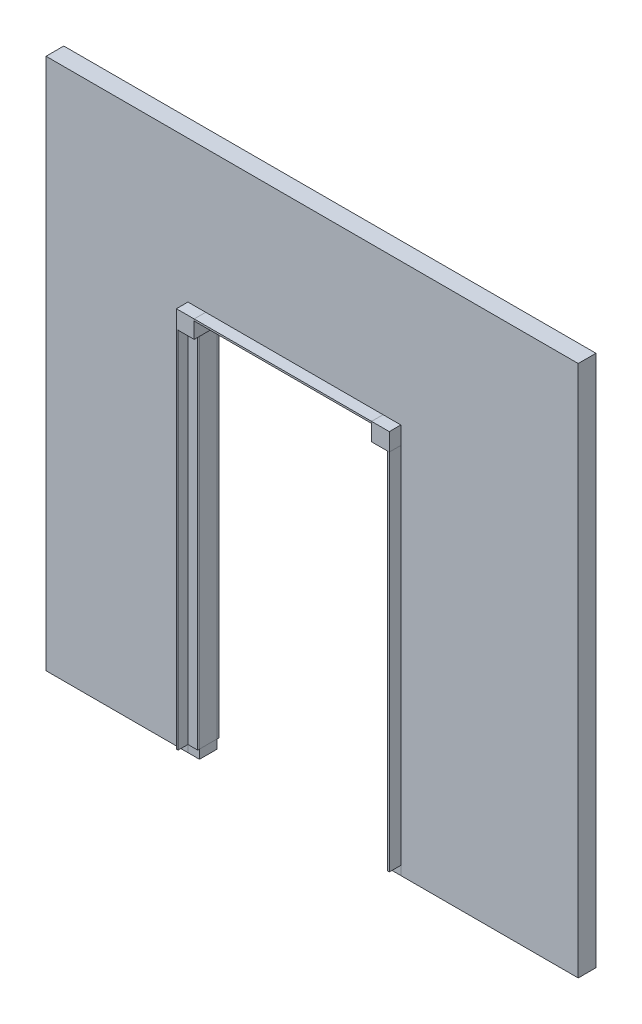
SolidWorks part; units mm, degrees
ref_plane "Front Plane" through (0, 0, 0) normal (0, 0, 1) x (1, 0, 0)
ref_plane "Top Plane" through (0, 0, 0) normal (0, 1, 0) x (1, 0, 0)
ref_plane "Right Plane" through (0, 0, 0) normal (1, 0, 0) x (0, 0, -1)
sketch "Sketch1" plane through (0, 0, 0) normal (0, 0, 1) x (1, 0, 0)
  line L1 (0, 0) -> (-3000, 0)
  line L2 (0, 0) -> (0, 3000)
  line L3 (0, 3000) -> (-3000, 3000)
  line L4 (-3000, 0) -> (-3000, 3000)
  line L5 (-2200, 2200) -> (-1000, 2200)
  line L6 (-2200, 2200) -> (-2200, 1300)
  line L7 (-2200, 1300) -> (-1000, 1300)
  line L8 (-1000, 2200) -> (-1000, 1300)
  dimension "D1" = 3000
  dimension "D2" = 3000
  dimension "D3" = 1300
  dimension "D4" = 1000
  dimension "D5" = 900
  dimension "D6" = 1200
extrude "Boss-Extrude1" add sketch "Sketch1" along normal blind 100
ref_plane "Plane4" through (0, 1750, 0) normal (0, -1, 0) x (-1, 0, 0)
ref_plane "Plane2" [suppressed] through (0, 0, 200) normal (0, 0, 1) x (1, 0, 0)
ref_plane "Plane1" through (-1600, 0, 0) normal (1, 0, 0) x (0, 0, -1)
ref_plane "Plane3" through (0, 2100, 0) normal (0, -1, 0) x (-1, 0, 0)
sketch "Sketch19" plane through (0, 0, 100) normal (0, 0, 1) x (1, 0, 0)
  line L14 (-2200, 2200) -> (-2100, 2200)
  line L15 (-2200, 2200) -> (-2200, 2100)
  line L16 (-2200, 2100) -> (-2100, 2100)
  line L17 (-2100, 2200) -> (-2100, 2100)
  line L18 (-1100, 2200) -> (-1100, 2100)
  line L19 (-1000, 2100) -> (-1100, 2100)
  line L20 (-1000, 2200) -> (-1000, 2100)
  line L21 (-1000, 2200) -> (-1100, 2200)
extrude "Boss-Extrude19" add sketch "Sketch19" along normal blind 65 and the other way blind 165 separate body
sketch "Sketch21" plane through (-2100, 0, 0) normal (1, 0, 0) x (0, 0, -1)
  line L17 (0, 2200) -> (0, 1300) construction
  line L18 (0, 2200) -> (0, 1300) construction
  line L20 (-165, 2200) -> (-100, 2200)
  line L21 (-100, 2200) -> (-100, 2135)
  line L22 (-100, 2135) -> (-110, 2135)
  line L23 (-110, 2135) -> (-110, 2190)
  line L24 (-110, 2190) -> (-165, 2190)
  line L25 (-165, 2190) -> (-165, 2200)
  line L26 (65, 2190) -> (65, 2200)
  line L27 (10, 2190) -> (65, 2190)
  line L28 (10, 2135) -> (10, 2190)
  line L29 (0, 2135) -> (10, 2135)
  line L30 (65, 2200) -> (0, 2200)
  line L31 (0, 2200) -> (0, 2135)
  line M37 (65, 2200) -> (-165, 2200)
  line M40 (65, 2100) -> (65, 2200)
sketch "Sketch22" plane through (0, 2100, 0) normal (0, -1, 0) x (1, 0, 0)
  line L0 (-1000, 100) -> (-1065, 100)
  line L2 (-1065, 100) -> (-1065, 110)
  line L3 (-1065, 110) -> (-1010, 110)
  line L4 (-1010, 110) -> (-1010, 165)
  line L5 (-1010, 165) -> (-1000, 165)
  line L7 (-1000, 165) -> (-1000, 100)
  line L8 (-1600, -55) -> (-1600, 55) construction
  line L9 (-2200, 165) -> (-2200, 100)
  line L10 (-2190, 165) -> (-2200, 165)
  line L11 (-2190, 110) -> (-2190, 165)
  line L12 (-2135, 110) -> (-2190, 110)
  line L13 (-2135, 100) -> (-2135, 110)
  line L14 (-2200, 100) -> (-2135, 100)
  line L15 (-3000, 50) -> (-548.5034, 50) construction
  line L16 (-3000, 100) -> (-3000, 0) construction
  line L17 (-2200, 0) -> (-2135, 0)
  line L18 (-2135, 0) -> (-2135, -10)
  line L19 (-2135, -10) -> (-2190, -10)
  line L20 (-2190, -10) -> (-2190, -65)
  line L21 (-2190, -65) -> (-2200, -65)
  line L22 (-2200, -65) -> (-2200, 0)
  line L23 (-1000, -65) -> (-1000, 0)
  line L24 (-1010, -65) -> (-1000, -65)
  line L25 (-1010, -10) -> (-1010, -65)
  line L26 (-1065, -10) -> (-1010, -10)
  line L27 (-1065, 0) -> (-1065, -10)
  line L28 (-1000, 0) -> (-1065, 0)
  dimension "D1" = 10
  dimension "D4" = 65
extrude "Boss-Extrude22" add sketch "Sketch22" along normal offset from surface (2050 mm away) 50 separate body contours L7 L0 L2 L3 L4 L5 | L23 L28 L27 L26 L25 L24 | L9 L14 L13 L12 L11 L10 | L17 L18 L19 L20 L21 L22 up to face at (-1500, 0, 50)
extrude "Boss-Extrude24" add sketch "Sketch21" along normal up to surface (1000 mm away) separate body contours L31 L29 L28 L27 M37 M40 | L20 L21 L22 L23 L24 L25 up to face at (-1100, 2150, 50)
sketch "Sketch23" plane through (0, 2100, 300) normal (0, -1, 0) x (1, 0, 0)
  line L0 (-1600, -355) -> (-1600, -245) construction
  line L1 (-1000, -200) -> (-1065, -200)
  line L2 (-1000, -200) -> (-1000, -300)
  line L3 (-1000, -300) -> (-1065, -300)
  line L4 (-1065, -200) -> (-1065, -300)
  line L5 (-2135, -200) -> (-2135, -300)
  line L6 (-2200, -300) -> (-2135, -300)
  line L7 (-2200, -200) -> (-2200, -300)
  line L8 (-2200, -200) -> (-2135, -200)
  dimension "D1" = 65
extrude "Boss-Extrude25" add sketch "Sketch23" along normal offset from surface (2050 mm away) 50 separate body up to face at (-1500, 0, 50)
sketch "Sketch24" plane through (0, 0, 100) normal (0, 0, 1) x (1, 0, 0)
  line L0 (-3000, 0) -> (0, 0) construction
  line L1 (-1000, 0) -> (-2200, 0)
  line L2 (-1000, 0) -> (-1000, 1300)
  line L3 (-1000, 1300) -> (-2200, 1300)
  line L4 (-2200, 0) -> (-2200, 1300)
  line L5 (-1000, 1300) -> (-1000, 2200) construction
  line L6 (-2200, 2200) -> (-2200, 1300) construction
  line L7 (-2200, 1300) -> (-1000, 1300) construction
extrude "Cut-Extrude1" cut sketch "Sketch24" against normal through all
sketch "Sketch25" plane through (0, 50, 0) normal (0, -1, 0) x (1, 0, 0)
  line L0 (-1000, 100) -> (-1065, 100) construction
  line L1 (-1065, 100) -> (-1065, 0) construction
  line L2 (-1065, 0) -> (-1000, 0) construction
  line L3 (-1000, 0) -> (-1000, 100) construction
  line L4 (-2200, 100) -> (-2200, 0) construction
  line L5 (-2200, 0) -> (-2135, 0) construction
  line L6 (-2135, 0) -> (-2135, 100) construction
  line L7 (-2135, 100) -> (-2200, 100) construction
  line L8 (-1000, 100) -> (-1065, 100)
  line L9 (-1065, 100) -> (-1065, 0)
  line L10 (-1065, 0) -> (-1000, 0)
  line L11 (-1000, 0) -> (-1000, 100)
  line L12 (-2200, 100) -> (-2200, 0)
  line L13 (-2200, 0) -> (-2135, 0)
  line L14 (-2135, 0) -> (-2135, 100)
  line L15 (-2135, 100) -> (-2200, 100)
extrude "Boss-Extrude26" add sketch "Sketch25" along normal blind 50 separate body
sketch "Sketch26" plane through (-2100, 0, 0) normal (1, 0, 0) x (0, 0, -1)
  line L1 (-100, 2200) -> (0, 2200)
  line L2 (-100, 2200) -> (-100, 2135)
  line L3 (-100, 2135) -> (0, 2135)
  line L4 (0, 2200) -> (0, 2135)
extrude "Boss-Extrude27" add sketch "Sketch26" along normal up to surface (1000 mm away) separate body up to face at (-1100, 2150, 50)
